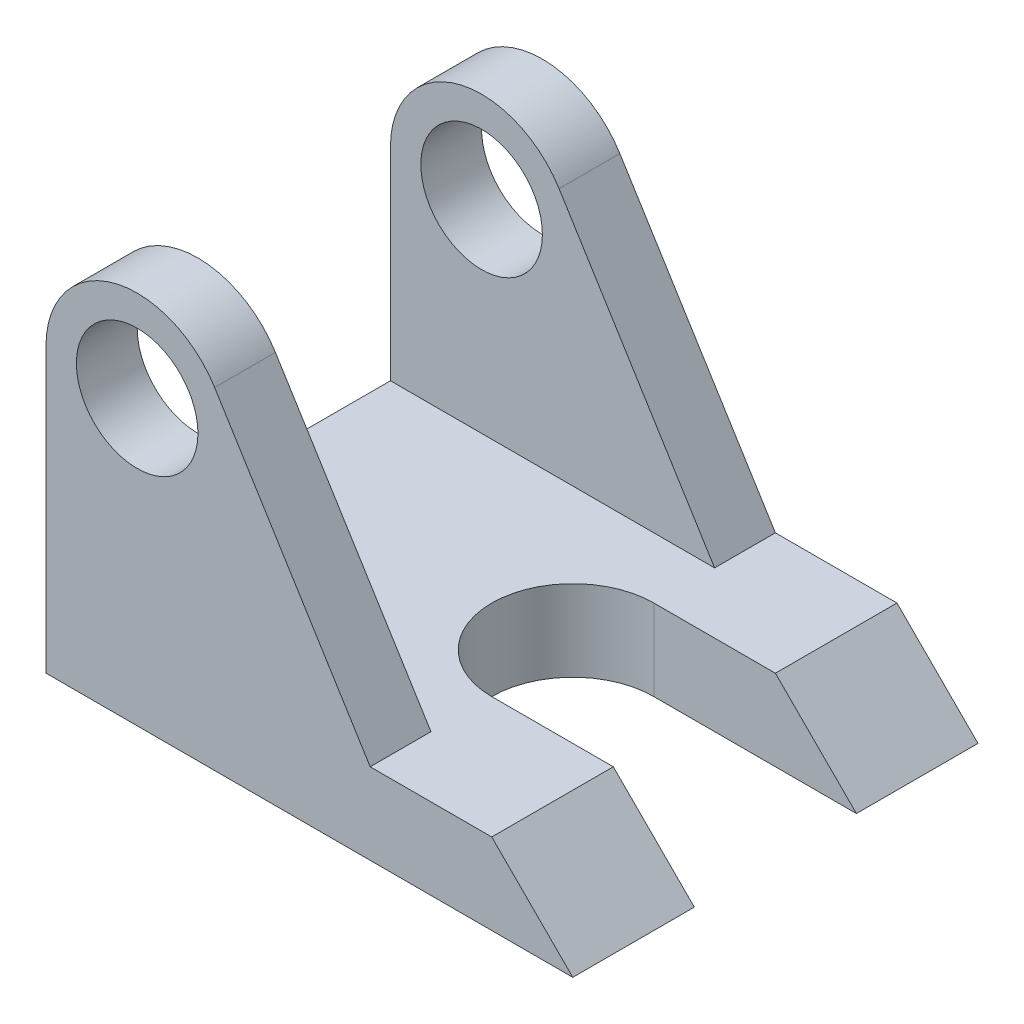
SolidWorks part; units mm, degrees
ref_plane "Front Plane" through (0, 0, 0) normal (0, 0, 1) x (1, 0, 0)
ref_plane "Top Plane" through (0, 0, 0) normal (0, 1, 0) x (1, 0, 0)
ref_plane "Right Plane" through (0, 0, 0) normal (1, 0, 0) x (0, 0, -1)
sketch "Sketch1" plane through (0, 0, 0) normal (0, 0, 1) x (1, 0, 0)
  line L0 (0, 0) -> (130, 0)
  line L1 (130, 0) -> (110, 20)
  line L2 (110, 20) -> (80, 20)
  line L3 (80, 20) -> (41.6192, 81.862)
  line L4 (0, 0) -> (0, 70)
  arc A1 (0, 70) -> (41.6192, 81.862) centre (22.5, 70) cw
  point P11 (0, 55.7774)
  dimension "D1" = 130
  dimension "D2" = 20
  dimension "D3" = 30
  dimension "D4" = 70
  dimension "D5" = 22.5
  dimension "D6" = 20
extrude "Boss-Extrude1" add sketch "Sketch1" along normal mid plane 100
sketch "Sketch2" plane through (0, 20, 0) normal (0, 1, 0) x (1, 0, 0)
  line L0 (80, 50) -> (41.6192, 50) construction
  line L1 (-10.0135, 35) -> (138.7664, 35)
  line L2 (-10.0135, 35) -> (-10.0135, -35)
  line L3 (-10.0135, -35) -> (138.7664, -35)
  line L4 (138.7664, 35) -> (138.7664, -35)
  line L5 (110, -50) -> (80, -50) construction
  dimension "D1" = 15
  dimension "D2" = 15
extrude "Cut-Extrude1" cut sketch "Sketch2" along normal through all
sketch "Sketch3" plane through (0, 20, 0) normal (0, 1, 0) x (1, 0, 0)
  line L0 (80, 20) -> (132.0674, 20)
  line L1 (132.0674, 20) -> (132.0674, -20)
  line L2 (132.0674, -20) -> (80, -20)
  line L3 (130, -50) -> (130, 50) construction
  arc A0 (80, 20) -> (80, -20) centre (80, 0) ccw
  point P1 (0, 0)
  dimension "D1" = 20
  dimension "D2" = 50
extrude "Cut-Extrude2" cut sketch "Sketch3" against normal through all
hole_wizard "Ø20.0mm Dowel Hole1" positions "Sketch4" profile "Sketch5" hole size "Ø20.0" standard "ISO" end condition through all
sketch "Sketch4" plane through (0, 0, 50) normal (0, 0, 1) x (1, 0, 0)
  point P0 (22.5, 70)
sketch "Sketch5" plane through (22.5, 70, 50) normal (1, 0, 0) x (0, -1, 0)
  line L0 (0, 0) -> (0, 100)
  line L1 (0, 100) -> (15, 100)
  line L2 (15, 100) -> (15, 0)
  line L5 (15, 0) -> (0, 0)
  line L11 (0, -6.35) -> (0, 107.95) construction
  dimension "Thru Hole Dia." = 30
  dimension "Thru Hole Depth" = 100
